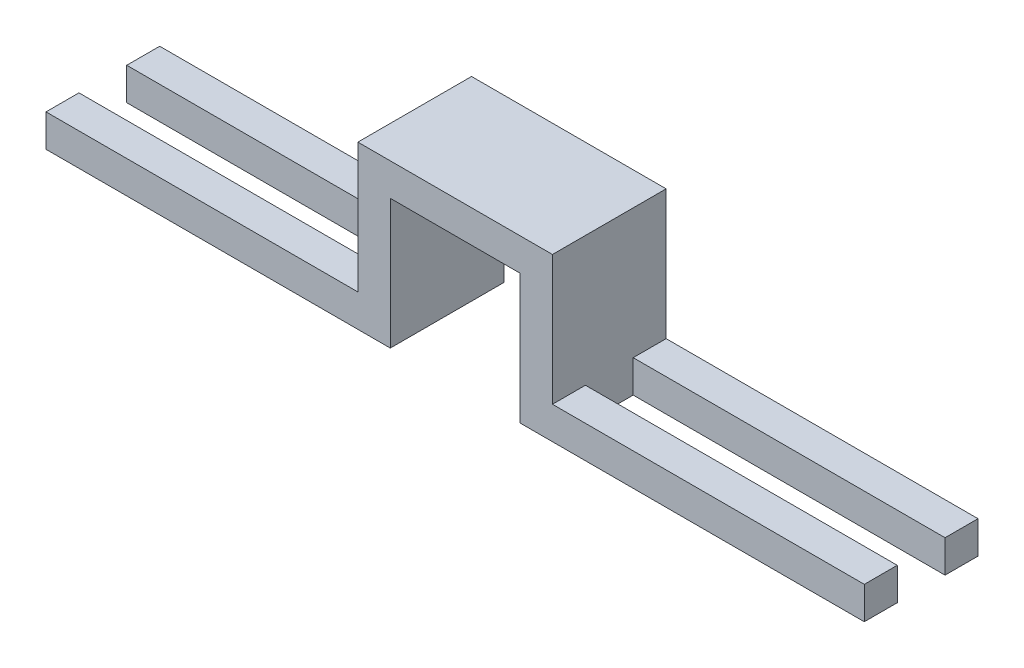
SolidWorks part; units mm, degrees
ref_plane "Front Plane" through (0, 0, 0) normal (0, 0, 1) x (1, 0, 0)
ref_plane "Top Plane" through (0, 0, 0) normal (0, 1, 0) x (1, 0, 0)
ref_plane "Right Plane" through (0, 0, 0) normal (1, 0, 0) x (0, 0, -1)
sketch "Sketch1" plane through (0, 0, 0) normal (0, 0, 1) x (1, 0, 0)
  line L0 (-10, -10) -> (-15, -10)
  line L1 (-10, -10) -> (10, -10)
  line L2 (-10, -10) -> (-10, 10)
  line L3 (-10, 10) -> (10, 10)
  line L4 (10, -10) -> (10, 10)
  line L5 (-10, -10) -> (10, 10) construction
  line L6 (-10, 10) -> (10, -10) construction
  line L8 (-15, -5) -> (-15, 15)
  line L9 (-15, 15) -> (15, 15)
  line L10 (15, -5) -> (15, 15)
  line L11 (-15, -15) -> (15, 15) construction
  line L12 (-15, 15) -> (15, -15) construction
  line L13 (10, -10) -> (15, -10)
  line L14 (0, -10) -> (0, -20.97)
  line L15 (-15, -10) -> (-63.0735, -10)
  line L17 (-15, -5) -> (-63.0735, -5)
  line L18 (-63.0735, -10) -> (-63.0735, -5)
  line L19 (15, -5) -> (63.0735, -5)
  line L20 (63.0735, -10) -> (63.0735, -5)
  line L21 (15, -10) -> (63.0735, -10)
  line L23 (-10, -10) -> (-15, -10)
  line L24 (15, -10) -> (10, -10)
  point P0 (0, 0)
  point P6 (0, 0)
  dimension "D1" = 20
  dimension "D2" = 20
  dimension "D3" = 5
  dimension "D4" = 5
  dimension "D5" = 5
extrude "Boss-Extrude1" add sketch "Sketch1" along normal blind 17.526 contours L13 L21 L20 L19 L10 L9 L8 L17 L18 L15 L0 L2 L3 L4
sketch "Sketch2" plane through (0, -5, 0) normal (0, 1, 0) x (1, 0, 0)
  line L0 (-15, -17.526) -> (-15, 0) construction
  line L1 (-15, -12.446) -> (-71.8933, -12.446)
  line L3 (-15, -5.08) -> (-71.8933, -5.08)
  line L4 (-71.8933, -12.446) -> (-71.8933, -5.08)
  line L5 (-15, -8.763) -> (-71.8933, -5.08) construction
  line L6 (-15, -8.763) -> (-71.8933, -12.446) construction
  line L7 (-15, -5.08) -> (-15, -12.446)
  line L8 (0, 0) -> (0, 12.2512)
  line L9 (-15, 0) -> (15, 0) construction
  line L10 (15, -5.08) -> (15, -12.446)
  line L11 (15, -12.446) -> (71.8933, -12.446)
  line L12 (71.8933, -12.446) -> (71.8933, -5.08)
  line L13 (15, -5.08) -> (71.8933, -5.08)
  point P0 (-15, -8.763)
  line M7 (-63.0735, 0) -> (-63.0735, -17.526)
  line M9 (-15, -17.526) -> (-15, 0)
  dimension "D1" = 7.366
extrude "Cut-Extrude1" cut sketch "Sketch2" against normal through all both and the other way through all contours L4 L1 L3 M7 | L3 L1 M9 M7 | L13 L10 L11 L12
